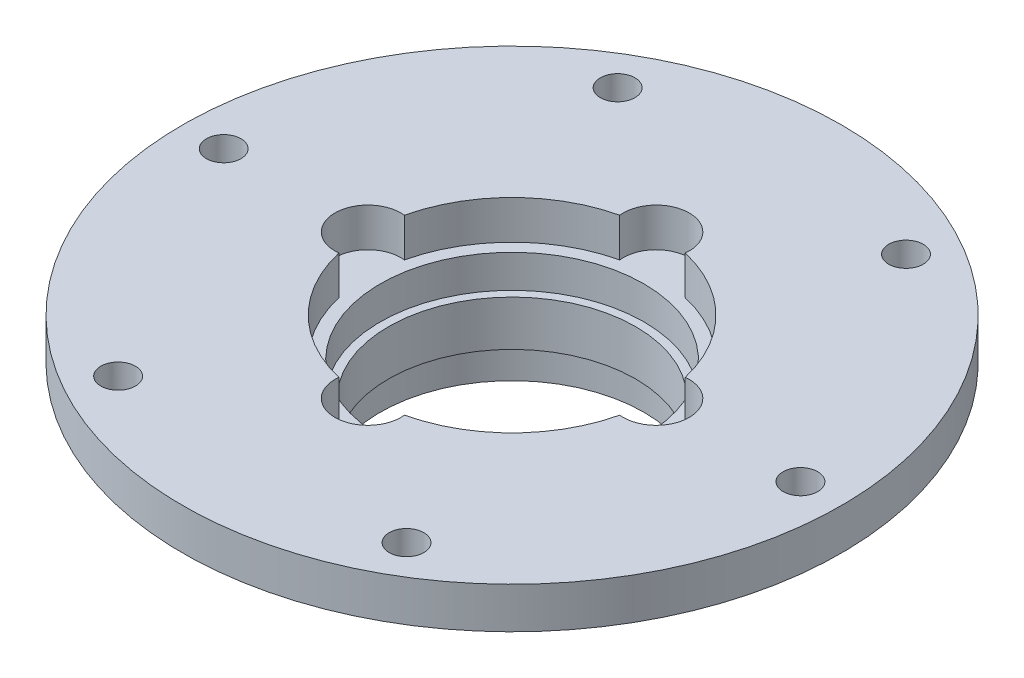
SolidWorks part; units mm, degrees
material "6061-T6 (SS)"
ref_plane "前视基准面" through (0, 0, 0) normal (0, 0, 1) x (1, 0, 0)
ref_plane "上视基准面" through (0, 0, 0) normal (0, 1, 0) x (1, 0, 0)
ref_plane "右视基准面" through (0, 0, 0) normal (1, 0, 0) x (0, 0, -1)
sketch "草图1" plane through (0, 0, 0) normal (0, 0, 1) x (1, 0, 0)
  line L0 (0, -49.6993) -> (0, -83.6993) construction
  line L1 (24, 12.2) -> (24, 6)
  line L2 (19, 0) -> (16, 0) construction
  line L3 (16, 0) -> (16, 3)
  line L4 (16, 3) -> (15, 3)
  line L5 (15, 3) -> (15, 8.5)
  line L6 (16, 12.5) -> (17.5, 12.5)
  line L7 (17.5, 12.5) -> (17.5, 17.2)
  line L8 (17.5, 17.2) -> (21.5, 17.2)
  line L9 (15, 8.5) -> (16, 8.5)
  line L10 (21.5, 17.2) -> (40, 17.2)
  line L11 (40, 17.2) -> (40, 12.2)
  line L12 (40, 12.2) -> (24, 12.2)
  line L13 (16, 8.5) -> (16, 12.5)
  line L16 (24, 6) -> (19, 6)
  line L17 (19, 6) -> (19, 0)
  line L18 (0, 0) -> (0, 23.9987) construction
  line L19 (19, 0) -> (19, -1)
  line L20 (19, -1) -> (16, -1)
  line L21 (16, -1) -> (16, 0)
  dimension "D2" = 48
  dimension "D3" = 35
  dimension "D4" = 4
  dimension "D5" = 5
  dimension "D6" = 22.5
  dimension "D7" = 11.2
  dimension "D8" = 6
  dimension "D10" = 3
  dimension "D11" = 12.5
  dimension "D12" = 5.5
  dimension "D13" = 38
  dimension "D14" = 1
  dimension "D15" = 1
  dimension "D16" = 3
revolve "旋转1" add sketch "草图1" angle 360 about L18
sketch "草图4" plane through (0, 17.2, 0) normal (0, 1, 0) x (1, 0, 0)
  circle A0 centre (0, 0) radius 17.5 construction
  circle A1 centre (0, -17.5) radius 4
  circle A2 centre (17.5, 0) radius 4
  circle A3 centre (0, 17.5) radius 4
  circle A4 centre (-17.5, 0) radius 4
  dimension "D1" = 35
  dimension "D2" = 8
  dimension "D3" = 8
  dimension "D4" = 8
  dimension "D5" = 8
extrude "切除-拉伸1" cut sketch "草图4" against normal up to surface (4.7 mm away) up to face at (0, 12.5, -16)
sketch "草图5" plane through (0, 17.2, 0) normal (0, 1, 0) x (1, 0, 0)
  circle A0 centre (0, 0) radius 35 construction
  point P5 (35, 0)
  point P7 (17.5, -30.3109)
  point P10 (-17.5, -30.3109)
  point P11 (-35, 0)
  point P12 (-17.5, 30.3109)
  point P13 (17.5, 30.3109)
  dimension "D1" = 70
  dimension "D2" = 6
hole_wizard "M5 螺纹孔1" positions "3D草图2" profile "草图7" tap size "M5" standard "GB" end condition through all
sketch3d "3D草图2"
  point P0 (17.5, 17.2, -30.3109)
  point P3 (35, 17.2, 0)
  point P6 (17.5, 17.2, 30.3109)
  point P9 (-17.5, 17.2, 30.3109)
  point P12 (-35, 17.2, 0)
  point P15 (-17.5, 17.2, -30.3109)
sketch "草图7" plane through (17.5, 17.2, -30.3109) normal (1, 0, 0) x (0, 0, 1)
  line L0 (0, 0) -> (0, 18.2)
  line L1 (0, 18.2) -> (2.1, 18.2)
  line L2 (2.1, 18.2) -> (2.1, 0)
  line L5 (2.1, 0) -> (0, 0)
  line L11 (0, -6.35) -> (0, 107.95) construction
  dimension "通孔螺纹孔钻头直径" = 4.2
  dimension "通孔螺纹孔钻头深度" = 18.2
cosmetic thread "孔螺蚊线1" parameters "D2"=5
cosmetic thread "孔螺蚊线2" parameters "D2"=5
cosmetic thread "孔螺蚊线3" parameters "D2"=5
cosmetic thread "孔螺蚊线4" parameters "D2"=5
cosmetic thread "孔螺蚊线5" parameters "D2"=5
cosmetic thread "孔螺蚊线6" parameters "D2"=5
equation "\"8。5\"=8"
equation "\"5。5\"=5.64244"
